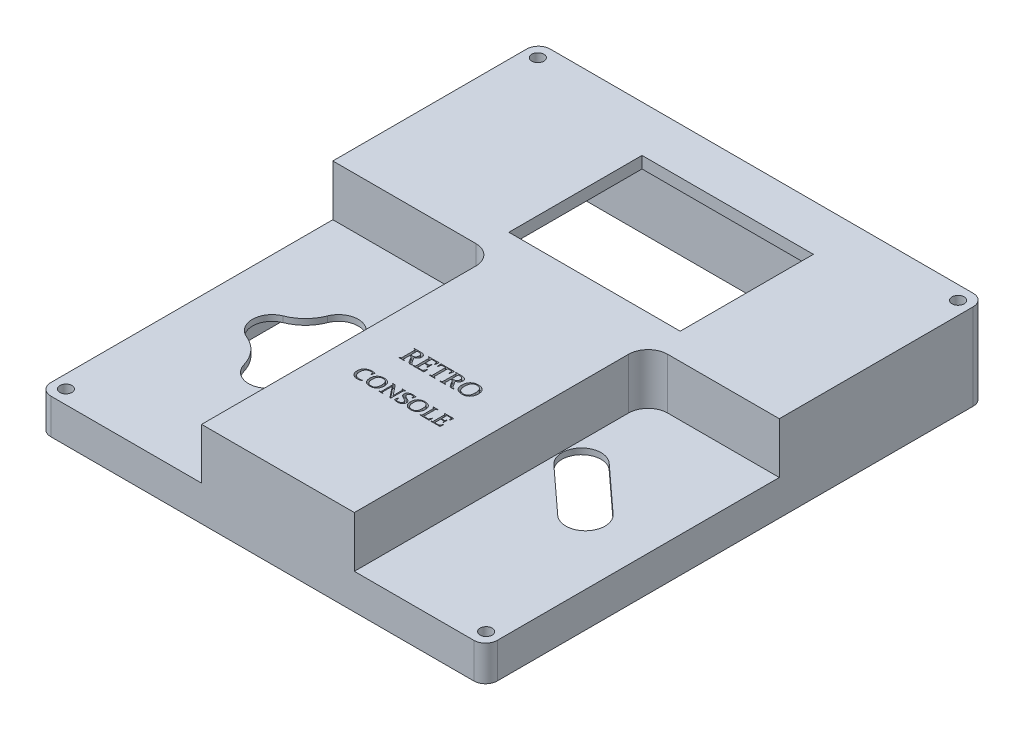
SolidWorks part; units mm, degrees
ref_plane "Front Plane" through (0, 0, 0) normal (0, 0, 1) x (1, 0, 0)
ref_plane "Top Plane" through (0, 0, 0) normal (0, 1, 0) x (1, 0, 0)
ref_plane "Right Plane" through (0, 0, 0) normal (1, 0, 0) x (0, 0, -1)
sketch "Croquis2" plane through (0, 0, 0) normal (0, 0, 1) x (1, 0, 0)
  line L0 (0, 0) -> (104, 0)
  line L1 (104, 0) -> (104, 22)
  line L2 (104, 22) -> (0, 22)
  line L3 (0, 22) -> (0, 0)
  dimension "D1" = 104
  dimension "D2" = 22
extrude "Saliente-Extruir1" add sketch "Croquis2" against normal blind 122.5
sketch "Croquis3" plane through (0, 0, 0) normal (0, 0, 1) x (1, 0, 0)
  line L0 (0, 0) -> (104, 0) construction
  line L3 (104, 22) -> (0, 22) construction
  line L4 (36.5, 22) -> (75.5, 22)
  line L7 (0, 22) -> (0, 0) construction
  line L8 (0, 9) -> (36.5, 9)
  line L9 (104, 0) -> (104, 22) construction
  line L13 (75.5, 9) -> (104, 9)
  line L14 (0, 9) -> (0, 22)
  line L15 (0, 22) -> (36.5, 22)
  line L16 (36.5, 22) -> (36.5, 9)
  line L17 (75.5, 9) -> (75.5, 22)
  line L18 (75.5, 22) -> (104, 22)
  line L19 (104, 22) -> (104, 9)
  dimension "D1" = 36.5
  dimension "D2" = 28.5
  dimension "D3" = 9
extrude "Cortar-Extruir1" cut sketch "Croquis3" against normal blind 75 contours L15 L14 L8 L16 | L17 L13 L19 L18
sketch "Croquis5" plane through (0, 0, 0) normal (0, -1, 0) x (1, 0, 0)
  line L4 (2, -2) -> (2, -120.5)
  line L6 (2, -2) -> (2, -120.5)
  line L8 (102, -2) -> (2, -2)
  line L9 (102, -120.5) -> (102, -2)
  line L10 (2, -120.5) -> (102, -120.5)
  line L11 (102, -120.5) -> (102, -2)
  line L12 (102, -2) -> (2, -2)
  line L14 (2, -120.5) -> (102, -120.5)
  dimension "D1" = 2
extrude "Cortar-Extruir3" cut sketch "Croquis5" against normal blind 7.5
sketch "Croquis6" plane through (0, 22, 0) normal (0, 1, 0) x (1, 0, 0)
  line L8 (102, 77) -> (102, 120.5)
  line L9 (102, 77) -> (102, 120.5)
  line L10 (2, 120.5) -> (2, 77)
  line L11 (2, 120.5) -> (2, 77)
  line L16 (2, 77) -> (38.5, 77)
  line L17 (38.5, 77) -> (38.5, 2)
  line L18 (38.5, 2) -> (73.5, 2)
  line L19 (73.5, 2) -> (73.5, 77)
  line L20 (73.5, 77) -> (102, 77)
  line L22 (102, 120.5) -> (2, 120.5)
  line L24 (2, 77) -> (38.5, 77)
  line L25 (38.5, 77) -> (38.5, 2)
  line L26 (38.5, 2) -> (73.5, 2)
  line L27 (73.5, 2) -> (73.5, 77)
  line L28 (73.5, 77) -> (102, 77)
  line L30 (102, 120.5) -> (2, 120.5)
  dimension "D1" = 2
sketch "Croquis7" plane through (0, 7.5, 0) normal (0, -1, 0) x (1, 0, 0)
  line L0 (2, -77) -> (38.5, -77)
  line L1 (102, -77) -> (102, -120.5)
  line L2 (102, -120.5) -> (2, -120.5)
  line L3 (2, -120.5) -> (2, -77)
  line L4 (38.5, -77) -> (38.5, -2)
  line L5 (38.5, -2) -> (73.5, -2)
  line L6 (73.5, -2) -> (73.5, -77)
  line L7 (73.5, -77) -> (102, -77)
extrude "Cortar-Extruir5" cut sketch "Croquis7" against normal blind 10
fillet "Redondeo1" radius 5 1 edges at (36.5, 15.5, -75)
fillet "Redondeo2" radius 5 1 edges at (75.5, 15.5, -75)
sketch "Croquis10" plane through (0, 9, 0) normal (0, 1, 0) x (1, 0, 0)
  line L0 (75.5, 0) -> (104, 0) construction
  line L1 (77.3749, 49.061) -> (89.1249, 38.311)
  line L3 (95.8751, 45.689) -> (84.1251, 56.439)
  line L4 (104, 75) -> (104, 0) construction
  arc A0 (89.1249, 38.311) -> (95.8751, 45.689) centre (92.5, 42) ccw
  arc A1 (84.1251, 56.439) -> (77.3749, 49.061) centre (80.75, 52.75) ccw
  dimension "D3" = 10
  dimension "D6" = 10
  dimension "D1" = 52.75
  dimension "D2" = 23.25
  dimension "D4" = 11.5
  dimension "D5" = 42
extrude "Cortar-Extruir6" cut sketch "Croquis10" against normal blind 7.5
sketch "Croquis11" plane through (0, 9, 0) normal (0, 1, 0) x (1, 0, 0)
  line L0 (0, 0) -> (36.5, 0) construction
  line L1 (0, 75) -> (0, 0) construction
  arc A0 (24.9564, 52.928) -> (15.594, 53.0626) centre (20.25, 51.24) ccw
  arc A1 (15.6951, 31.6169) -> (25.3148, 31.6516) centre (20.5, 33) ccw
  arc A2 (30.6481, 37.9849) -> (30.4564, 47.1013) centre (28.5, 42.5) ccw
  arc A3 (9.9274, 47.396) -> (9.8618, 38.1103) centre (11.75, 42.74) ccw
  arc A4 (9.9274, 47.396) -> (15.594, 53.0626) centre (6.2821, 56.7079) ccw
  arc A5 (9.8618, 38.1103) -> (15.6951, 31.6169) centre (6.0853, 28.8508) cw
  arc A6 (25.3148, 31.6516) -> (30.6481, 37.9849) centre (34.9443, 28.9548) cw
  arc A7 (30.4564, 47.1013) -> (24.9564, 52.928) centre (34.3693, 56.304) cw
  dimension "D1" = 10
  dimension "D10" = 10
  dimension "D11" = 10
  dimension "D12" = 10
  dimension "D13" = 10
  dimension "D14" = 10
  dimension "D15" = 10
  dimension "D16" = 10
  dimension "D2" = 33
  dimension "D3" = 42.5
  dimension "D4" = 42.74
  dimension "D5" = 51.24
  dimension "D6" = 20.5
  dimension "D7" = 28.5
  dimension "D8" = 11.75
  dimension "D9" = 20.25
extrude "Cortar-Extruir7" cut sketch "Croquis11" against normal blind 7.5
sketch "Croquis12" plane through (0, 22, 0) normal (0, 1, 0) x (1, 0, 0)
  line L0 (33.25, 81.7) -> (77, 81.7)
  line L1 (77, 81.7) -> (77, 115.7)
  line L2 (77, 115.7) -> (33.25, 115.7)
  line L3 (33.25, 115.7) -> (33.25, 81.7)
  line L4 (75.5, 0) -> (36.5, 0) construction
  line L5 (0, 122.5) -> (0, 75) construction
  line L6 (104, 122.5) -> (104, 75) construction
  dimension "D1" = 81.7
  dimension "D2" = 33.25
  dimension "D3" = 27
  dimension "D4" = 34
extrude "Cortar-Extruir8" cut sketch "Croquis12" against normal blind 7.5
sketch "Croquis30" plane through (0, 17.5, 0) normal (0, -1, 0) x (1, 0, 0)
  line L0 (38.5, -2) -> (73.5, -2)
  line L1 (73.5, -2) -> (73.5, -77)
  line L2 (73.5, -77) -> (102, -77)
  line L3 (102, -77) -> (102, -120.5)
  line L4 (102, -120.5) -> (2, -120.5)
  line L5 (2, -120.5) -> (2, -77)
  line L6 (2, -77) -> (38.5, -77)
  line L7 (38.5, -77) -> (38.5, -2)
extrude "Cortar-Extruir9" cut sketch "Croquis30" against normal blind 3
sketch "Croquis31" plane through (104, 0, 0) normal (1, 0, 0) x (0, 0, -1)
  line L0 (122.5, 0) -> (122.5, 22)
  line L1 (122.5, 22) -> (75, 22)
  line L2 (75, 22) -> (75, 9)
  line L3 (75, 9) -> (0, 9)
  line L4 (0, 9) -> (0, 0)
  line L5 (0, 0) -> (122.5, 0)
extrude "Saliente-Extruir3" add sketch "Croquis31" along normal blind 5
sketch "Croquis32" plane through (0, 0, 0) normal (-1, 0, 0) x (0, 0, 1)
  line L0 (0, 0) -> (-122.5, 0)
  line L1 (-122.5, 0) -> (-122.5, 22)
  line L2 (-122.5, 22) -> (-75, 22)
  line L3 (-75, 22) -> (-75, 9)
  line L4 (-75, 9) -> (0, 9)
  line L5 (0, 9) -> (0, 0)
extrude "Saliente-Extruir4" add sketch "Croquis32" along normal blind 5
sketch "Croquis33" plane through (0, 0, -122.5) normal (0, 0, -1) x (-1, 0, 0)
  line L0 (5, 0) -> (-109, 0)
  line L1 (-109, 0) -> (-109, 22)
  line L2 (-109, 22) -> (5, 22)
  line L3 (5, 22) -> (5, 0)
extrude "Saliente-Extruir5" add sketch "Croquis33" along normal blind 5
fillet "Redondeo3" radius 3 4 edges at (-5, 11, -127.5) (109, 11, -127.5) (-5, 4.5, 0) (109, 4.5, 0)
sketch "Croquis34" plane through (0, 22, 0) normal (0, 1, 0) x (1, 0, 0)
  line L0 (-5, 75) -> (-5, 124.5) construction
  line L1 (-2, 127.5) -> (106, 127.5) construction
  line L2 (-5, 3) -> (-5, 75) construction
  line L3 (-2, 0) -> (36.5, 0) construction
  line L4 (75.5, 0) -> (106, 0) construction
  line L5 (109, 75) -> (109, 3) construction
  line L7 (109, 124.5) -> (109, 75) construction
  circle A0 centre (-1.65, 124) radius 1.55
  circle A2 centre (105.65, 3.5) radius 1.55
  circle A3 centre (-1.65, 3.5) radius 1.55
  circle A4 centre (105.65, 124) radius 1.55
  dimension "D1" = 3.1
  dimension "D2" = 3.1
  dimension "D3" = 3.1
  dimension "D4" = 3.1
  dimension "D5" = 3.35
  dimension "D6" = 3.5
  dimension "D7" = 3.35
  dimension "D8" = 3.5
  dimension "D9" = 3.5
  dimension "D10" = 3.35
  dimension "D11" = 3.35
  dimension "D12" = 3.5
extrude "Cortar-Extruir10" cut sketch "Croquis34" against normal through all
sketch "Croquis35" plane through (0, 20.5, 0) normal (0, -1, 0) x (1, 0, 0)
  line L0 (31.75, -80.2) -> (78.5, -80.2)
  line L1 (78.5, -80.2) -> (78.5, -117.2)
  line L2 (78.5, -117.2) -> (31.75, -117.2)
  line L3 (31.75, -117.2) -> (31.75, -80.2)
  line L4 (33.25, -81.7) -> (33.25, -115.7) construction
  line L5 (77, -81.7) -> (33.25, -81.7) construction
  line L6 (33.25, -115.7) -> (77, -115.7) construction
  line L7 (77, -115.7) -> (77, -81.7) construction
  line L9 (33.25, -81.7) -> (77, -81.7)
  line L10 (33.25, -81.7) -> (33.25, -115.7)
  line L11 (33.25, -115.7) -> (77, -115.7)
  line L12 (77, -81.7) -> (77, -115.7)
  dimension "D1" = 1.5
  dimension "D2" = 1.5
  dimension "D3" = 1.5
  dimension "D4" = 1.5
extrude "Saliente-Extruir6" add sketch "Croquis35" along normal blind 1.5
sketch "Croquis36" plane through (0, 22, 0) normal (0, 1, 0) x (1, 0, 0)
  line L0 (36.5, 40) -> (75.5, 40) construction
  line L1 (36.5, 70) -> (36.5, 0) construction
  line L2 (75.5, 70) -> (75.5, 0) construction
  line L3 (75.5, 0) -> (36.5, 0) construction
  line L4 (36.5, 30) -> (75.5, 30) construction
  line L5 (36.5, 70) -> (36.5, 0) construction
  text T0 "RETRO" font "Constantia" height 4
  text T1 "CONSOLE" font "Constantia" height 3.5
  dimension "D1" = 40
  dimension "D2" = 30
extrude "Cortar-Extruir11" cut sketch "Croquis36" against normal blind 1
